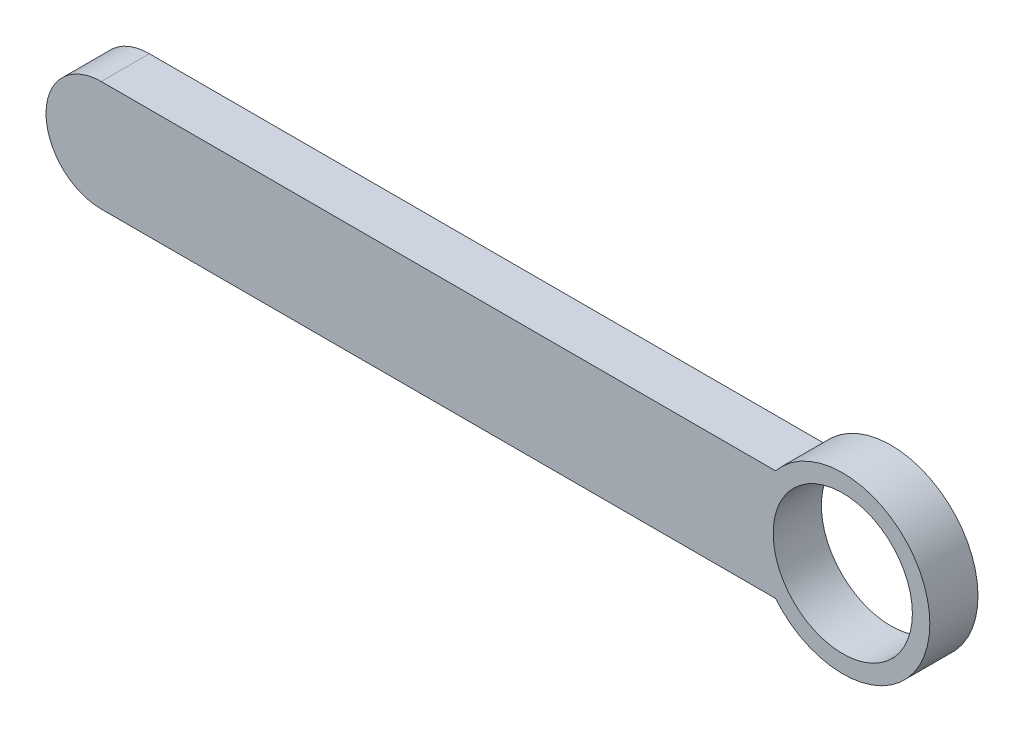
SolidWorks part; units mm, degrees
ref_plane "Front Plane" through (0, 0, 0) normal (0, 0, 1) x (1, 0, 0)
ref_plane "Top Plane" through (0, 0, 0) normal (0, 1, 0) x (1, 0, 0)
ref_plane "Right Plane" through (0, 0, 0) normal (1, 0, 0) x (0, 0, -1)
sketch "Sketch1" plane through (0, 0, 0) normal (0, 0, 1) x (1, 0, 0)
  line L1 (-3.8675, 3.175) -> (-42.6212, 3.175)
  line L3 (-3.8675, -3.175) -> (-42.6212, -3.175)
  arc A0 (-3.8675, -3.175) -> (-3.8675, 3.175) centre (0, 0) ccw
  circle A1 centre (0, 0) radius 4.0005
  arc A2 (-42.6212, -3.175) -> (-42.6212, 3.175) centre (-42.6212, 0) cw
  point P1 (-45.7962, 0)
  point P6 (5.0038, 0)
  dimension "D1" = 8.001
  dimension "D2" = 10.0076
  dimension "D3" = 50.8
  dimension "D4" = 6.35
extrude "Boss-Extrude1" add sketch "Sketch1" along normal blind 2.7686
